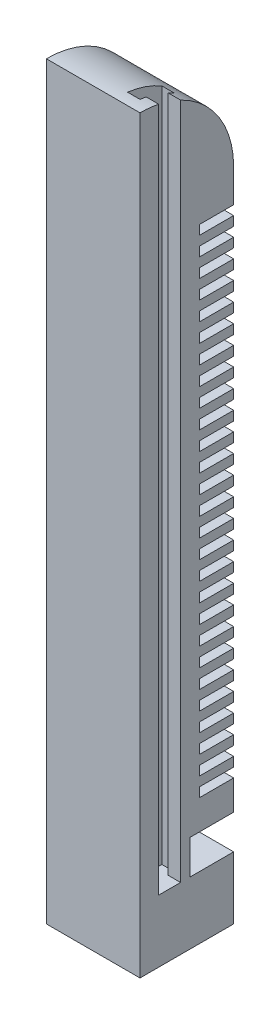
SolidWorks part; units mm, degrees
material "Alumina"
ref_plane "Front Plane" through (0, 0, 0) normal (0, 0, 1) x (1, 0, 0)
ref_plane "Top Plane" through (0, 0, 0) normal (0, 1, 0) x (1, 0, 0)
ref_plane "Right Plane" through (0, 0, 0) normal (1, 0, 0) x (0, 0, -1)
sketch "Sketch1" plane through (0, 0, 0) normal (0, 1, 0) x (1, 0, 0)
  line L1 (0, 0) -> (15, 0)
  line L2 (0, 0) -> (0, 15)
  line L3 (0, 15) -> (15, 15)
  line L4 (15, 0) -> (15, 15)
  dimension "D1" = 15
  dimension "D2" = 15
extrude "Boss-Extrude1" add sketch "Sketch1" along normal blind 120
sketch "Sketch3" plane through (0, 120, 0) normal (0, 1, 0) x (1, 0, 0)
  line L0 (15, 3) -> (13, 3)
  line L1 (15, 0) -> (15, 15) construction
  line L2 (13, 3) -> (13, 2)
  line L3 (13, 2) -> (11, 2)
  line L4 (11, 2) -> (11, 7.5)
  line L5 (11, 7.5) -> (13, 7.5)
  line L6 (13, 7.5) -> (13, 6.5)
  line L7 (13, 6.5) -> (15, 6.5)
  line L8 (15, 6.5) -> (15, 3)
  line L9 (15, 15) -> (0, 0) construction
  line L10 (3, 13) -> (2, 13)
  line L11 (6.5, 15) -> (3, 15)
  line L12 (7.5, 13) -> (6.5, 13)
  line L13 (6.5, 13) -> (6.5, 15)
  line L14 (7.5, 11) -> (7.5, 13)
  line L15 (2, 11) -> (7.5, 11)
  line L16 (2, 13) -> (2, 11)
  line L17 (3, 15) -> (3, 13)
  dimension "D1" = 3
  dimension "D2" = 5.5
  dimension "D3" = 3.5
  dimension "D4" = 1
  dimension "D5" = 2
  dimension "D6" = 2
extrude "Cut-Extrude1" cut sketch "Sketch3" against normal blind 110
sketch "Sketch5" plane through (0, 120, 0) normal (0, 1, 0) x (1, 0, 0)
  line L0 (15, 15) -> (15, 9.5)
  line L2 (15, 9.5) -> (9.5, 15)
  line L4 (9.5, 15) -> (15, 15)
  dimension "D1" = 5.5
  dimension "D2" = 5.5
extrude "Cut-Extrude2" cut sketch "Sketch5" against normal blind 1.5 from offset 20.25 offset against normal yes
pattern_linear "LPattern1" count 27 spacing 3 along (0, -1, 0) of "Cut-Extrude2"
sketch "Sketch6" plane through (0, 0, 0) normal (0, -1, 0) x (1, 0, 0)
  line L5 (15, -15) -> (8, -15)
  line L9 (15, -8) -> (15, -15)
  line L10 (8, -15) -> (8, -8)
  line L11 (8, -8) -> (15, -8)
  dimension "D1" = 7
  dimension "D2" = 7
extrude "Cut-Extrude3" cut sketch "Sketch6" against normal blind 5.5 from offset 10 offset against normal yes
sketch "Sketch7" plane through (0, 0, 0) normal (-1, 0, 0) x (0, 0, 1)
  line L0 (0, 120) -> (0, 110) construction
  line L1 (0, 120) -> (0, 0) construction
  line L2 (-15, 120) -> (-15, 0) construction
  line L3 (-15, 120) -> (0, 120) construction
  line L4 (-15, 105) -> (-15, 120)
  line L5 (-15, 120) -> (0, 120)
  arc A0 (-15, 105) -> (0, 120) centre (0, 105) cw
  dimension "D1" = 10
extrude "Cut-Extrude4" cut sketch "Sketch7" against normal through all
